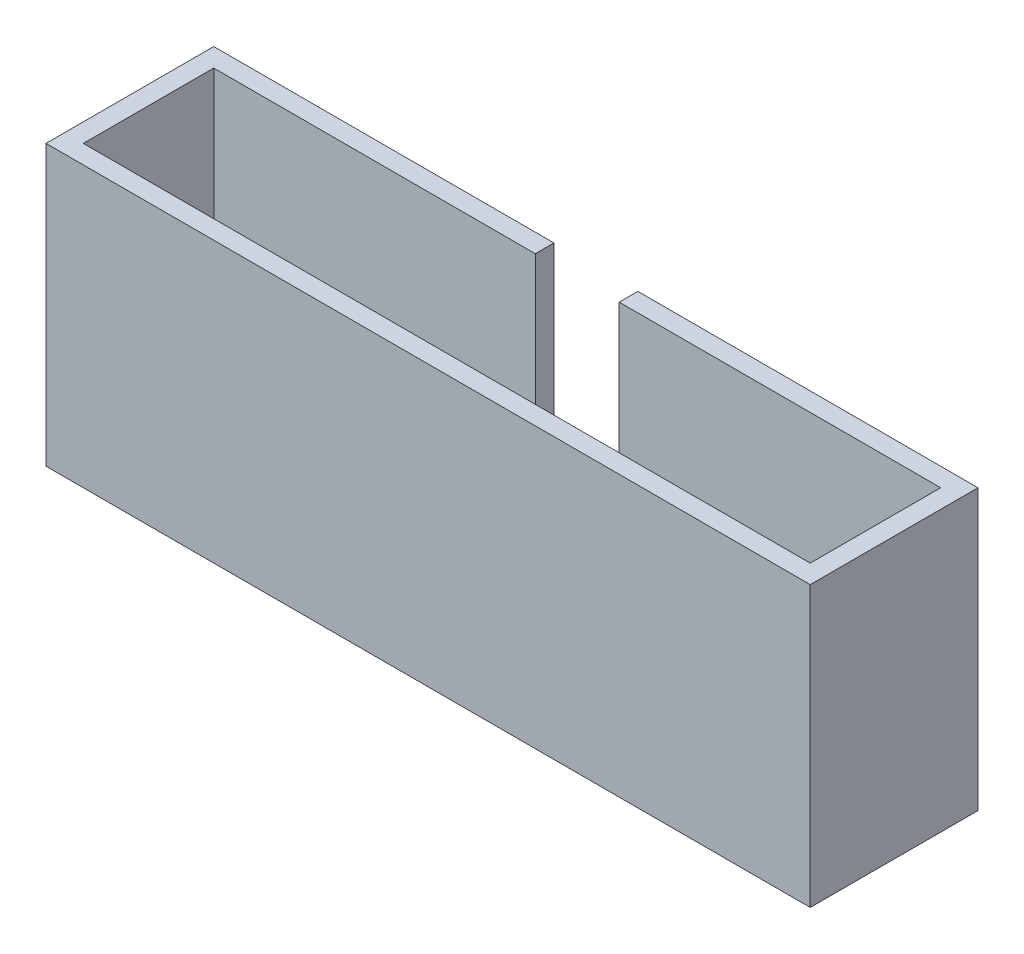
SolidWorks part; units mm, degrees
ref_plane "前视基准面" through (0, 0, 0) normal (0, 0, 1) x (1, 0, 0)
ref_plane "上视基准面" through (0, 0, 0) normal (0, 1, 0) x (1, 0, 0)
ref_plane "右视基准面" through (0, 0, 0) normal (1, 0, 0) x (0, 0, -1)
sketch "底图" plane through (0, 0, 0) normal (0, 1, 0) x (1, 0, 0)
  line L1 (19.5, -3.5) -> (-19.5, -3.5)
  line L2 (19.5, -3.5) -> (19.5, 3.5)
  line L3 (19.5, 3.5) -> (-19.5, 3.5)
  line L4 (-19.5, -3.5) -> (-19.5, 3.5)
  line L5 (19.5, -3.5) -> (-19.5, 3.5) construction
  line L6 (19.5, 3.5) -> (-19.5, -3.5) construction
  line L7 (20.5, -4.5) -> (-20.5, -4.5)
  line L8 (20.5, -4.5) -> (20.5, 4.5)
  line L9 (20.5, 4.5) -> (-20.5, 4.5)
  line L10 (-20.5, -4.5) -> (-20.5, 4.5)
  line L11 (20.5, -4.5) -> (-20.5, 4.5) construction
  line L12 (20.5, 4.5) -> (-20.5, -4.5) construction
  line L13 (2.25, -4.5) -> (-2.25, -4.5)
  line L14 (2.25, -4.5) -> (2.25, 4.5)
  line L15 (2.25, 4.5) -> (-2.25, 4.5)
  line L16 (-2.25, -4.5) -> (-2.25, 4.5)
  line L17 (2.25, -4.5) -> (-2.25, 4.5) construction
  line L18 (2.25, 4.5) -> (-2.25, -4.5) construction
  line L19 (-15, -1.25) -> (15, -1.25)
  line L20 (-15, -1.25) -> (-15, 1.25)
  line L21 (-15, 1.25) -> (15, 1.25)
  line L22 (15, -1.25) -> (15, 1.25)
  line L23 (-15, -1.25) -> (15, 1.25) construction
  line L24 (-15, 1.25) -> (15, -1.25) construction
  point P0 (0, 0)
  point P6 (0, 0)
  point P11 (0, 0)
  point P16 (0, 0)
  dimension "D1" = 7
  dimension "D2" = 39
  dimension "D3" = 41
  dimension "D4" = 9
  dimension "D5" = 4.5
  dimension "D6" = 9
  dimension "D7" = 2.5
  dimension "D8" = 30
sketch "基体" plane through (0, 0, 0) normal (0, 1, 0) x (1, 0, 0)
  line L4 (-2.25, -4.5) -> (2.25, -4.5)
  line L5 (-2.25, 4.5) -> (-2.25, -4.5)
  line L6 (2.25, 4.5) -> (-2.25, 4.5)
  line L7 (2.25, -4.5) -> (2.25, 4.5)
  line L8 (-2.25, -4.5) -> (2.25, -4.5)
  line L10 (2.25, 4.5) -> (-2.25, 4.5)
  line L12 (-20.5, -4.5) -> (20.5, -4.5)
  line L13 (-20.5, 4.5) -> (-20.5, -4.5)
  line L14 (20.5, 4.5) -> (-20.5, 4.5)
  line L15 (20.5, -4.5) -> (20.5, 4.5)
  line L16 (-20.5, -4.5) -> (20.5, -4.5)
  line L17 (-20.5, 4.5) -> (-20.5, -4.5)
  line L18 (20.5, 4.5) -> (-20.5, 4.5)
  line L19 (20.5, -4.5) -> (20.5, 4.5)
  dimension "D1" = 0
  dimension "D2" = 0
extrude "基体-凸台-拉伸" add sketch "基体" along normal blind 15 contours L16 L19 L18 L10 L17 L8
sketch "草图4" plane through (0, 0, 0) normal (0, 1, 0) x (1, 0, 0)
  line L1 (19.5, -3.5) -> (-19.5, -3.5)
  line L2 (19.5, -3.5) -> (19.5, 3.5)
  line L3 (19.5, 3.5) -> (-19.5, 3.5)
  line L4 (-19.5, -3.5) -> (-19.5, 3.5)
  line L5 (19.5, -3.5) -> (-19.5, 3.5) construction
  line L6 (19.5, 3.5) -> (-19.5, -3.5) construction
  point P0 (0, 0)
  dimension "D1" = 7
  dimension "D2" = 39
extrude "切除-拉伸8" cut sketch "草图4" against normal blind 10 from offset 15
sketch "草图5" plane through (0, 15, 0) normal (0, 1, 0) x (1, 0, 0)
  line L0 (-2.25, 0) -> (2.25, 0)
  line L2 (2.25, 0) -> (2.25, 6.901)
  line L3 (2.25, 6.901) -> (-2.25, 6.901)
  line L4 (-2.25, 0) -> (-2.25, 6.901)
  line L5 (0, 0) -> (-2.25, 6.901) construction
  line L6 (2.25, 6.901) -> (0, 0) construction
  point P0 (0, 0)
  dimension "D1" = 4.5
extrude "切除-拉伸9" cut sketch "草图5" against normal blind 10
sketch "草图6" plane through (0, 5, 0) normal (0, 1, 0) x (1, 0, 0)
  line L0 (2.25, 1.75) -> (2.75, 1.75)
  line L1 (2.75, 1.25) -> (2.75, 1.75)
  line L2 (-0.25, 1.25) -> (0.25, 1.25)
  line L3 (-0.25, 1.25) -> (-0.25, 1.75)
  line L4 (-0.25, 1.75) -> (0.25, 1.75)
  line L5 (0.25, 1.25) -> (0.25, 1.75)
  line L6 (-0.25, 1.25) -> (0.25, 1.75) construction
  line L7 (-0.25, 1.75) -> (0.25, 1.25) construction
  line L8 (2.25, 1.25) -> (2.75, 1.25)
  line L9 (2.25, 1.25) -> (2.25, 1.75)
  line L10 (4.75, 1.75) -> (5.25, 1.75)
  line L11 (5.25, 1.25) -> (5.25, 1.75)
  line L12 (4.75, 1.25) -> (5.25, 1.25)
  line L13 (4.75, 1.25) -> (4.75, 1.75)
  line L14 (7.25, 1.75) -> (7.75, 1.75)
  line L15 (7.75, 1.25) -> (7.75, 1.75)
  line L16 (7.25, 1.25) -> (7.75, 1.25)
  line L17 (7.25, 1.25) -> (7.25, 1.75)
  line L18 (9.75, 1.75) -> (10.25, 1.75)
  line L19 (10.25, 1.25) -> (10.25, 1.75)
  line L20 (9.75, 1.25) -> (10.25, 1.25)
  line L21 (9.75, 1.25) -> (9.75, 1.75)
  line L22 (12.25, 1.75) -> (12.75, 1.75)
  line L23 (12.75, 1.25) -> (12.75, 1.75)
  line L24 (12.25, 1.25) -> (12.75, 1.25)
  line L25 (12.25, 1.25) -> (12.25, 1.75)
  line L26 (14.75, 1.75) -> (15.25, 1.75)
  line L27 (15.25, 1.25) -> (15.25, 1.75)
  line L28 (14.75, 1.25) -> (15.25, 1.25)
  line L29 (14.75, 1.25) -> (14.75, 1.75)
  line L30 (-0.25, 1.75) -> (0.25, 1.75)
  line L31 (0.25, 1.25) -> (0.25, 1.75)
  line L32 (-0.25, 1.25) -> (0.25, 1.25)
  line L33 (-0.25, 1.25) -> (-0.25, 1.75)
  line L34 (2.25, 1.75) -> (2.75, 1.75)
  line L35 (2.75, 1.25) -> (2.75, 1.75)
  line L36 (2.25, 1.25) -> (2.75, 1.25)
  line L37 (2.25, 1.25) -> (2.25, 1.75)
  line L38 (4.75, 1.75) -> (5.25, 1.75)
  line L39 (5.25, 1.25) -> (5.25, 1.75)
  line L40 (4.75, 1.25) -> (5.25, 1.25)
  line L41 (4.75, 1.25) -> (4.75, 1.75)
  line L42 (7.25, 1.75) -> (7.75, 1.75)
  line L43 (7.75, 1.25) -> (7.75, 1.75)
  line L44 (7.25, 1.25) -> (7.75, 1.25)
  line L45 (7.25, 1.25) -> (7.25, 1.75)
  line L46 (9.75, 1.75) -> (10.25, 1.75)
  line L47 (10.25, 1.25) -> (10.25, 1.75)
  line L48 (9.75, 1.25) -> (10.25, 1.25)
  line L49 (9.75, 1.25) -> (9.75, 1.75)
  line L50 (12.25, 1.75) -> (12.75, 1.75)
  line L51 (12.75, 1.25) -> (12.75, 1.75)
  line L52 (12.25, 1.25) -> (12.75, 1.25)
  line L53 (12.25, 1.25) -> (12.25, 1.75)
  line L54 (-2.75, 1.75) -> (-2.25, 1.75)
  line L55 (-2.25, 1.25) -> (-2.25, 1.75)
  line L56 (-2.75, 1.25) -> (-2.25, 1.25)
  line L57 (-2.75, 1.25) -> (-2.75, 1.75)
  line L58 (-0.25, 1.75) -> (0.25, 1.75)
  line L59 (0.25, 1.25) -> (0.25, 1.75)
  line L60 (-0.25, 1.25) -> (0.25, 1.25)
  line L61 (-0.25, 1.25) -> (-0.25, 1.75)
  line L62 (2.25, 1.75) -> (2.75, 1.75)
  line L63 (2.75, 1.25) -> (2.75, 1.75)
  line L64 (2.25, 1.25) -> (2.75, 1.25)
  line L65 (2.25, 1.25) -> (2.25, 1.75)
  line L66 (4.75, 1.75) -> (5.25, 1.75)
  line L67 (5.25, 1.25) -> (5.25, 1.75)
  line L68 (4.75, 1.25) -> (5.25, 1.25)
  line L69 (4.75, 1.25) -> (4.75, 1.75)
  line L70 (7.25, 1.75) -> (7.75, 1.75)
  line L71 (7.75, 1.25) -> (7.75, 1.75)
  line L72 (7.25, 1.25) -> (7.75, 1.25)
  line L73 (7.25, 1.25) -> (7.25, 1.75)
  line L74 (9.75, 1.75) -> (10.25, 1.75)
  line L75 (10.25, 1.25) -> (10.25, 1.75)
  line L76 (9.75, 1.25) -> (10.25, 1.25)
  line L77 (9.75, 1.25) -> (9.75, 1.75)
  line L78 (-5.25, 1.75) -> (-4.75, 1.75)
  line L79 (-4.75, 1.25) -> (-4.75, 1.75)
  line L80 (-5.25, 1.25) -> (-4.75, 1.25)
  line L81 (-5.25, 1.25) -> (-5.25, 1.75)
  line L82 (-2.75, 1.75) -> (-2.25, 1.75)
  line L83 (-2.25, 1.25) -> (-2.25, 1.75)
  line L84 (-2.75, 1.25) -> (-2.25, 1.25)
  line L85 (-2.75, 1.25) -> (-2.75, 1.75)
  line L86 (-0.25, 1.75) -> (0.25, 1.75)
  line L87 (0.25, 1.25) -> (0.25, 1.75)
  line L88 (-0.25, 1.25) -> (0.25, 1.25)
  line L89 (-0.25, 1.25) -> (-0.25, 1.75)
  line L90 (2.25, 1.75) -> (2.75, 1.75)
  line L91 (2.75, 1.25) -> (2.75, 1.75)
  line L92 (2.25, 1.25) -> (2.75, 1.25)
  line L93 (2.25, 1.25) -> (2.25, 1.75)
  line L94 (4.75, 1.75) -> (5.25, 1.75)
  line L95 (5.25, 1.25) -> (5.25, 1.75)
  line L96 (4.75, 1.25) -> (5.25, 1.25)
  line L97 (4.75, 1.25) -> (4.75, 1.75)
  line L98 (7.25, 1.75) -> (7.75, 1.75)
  line L99 (7.75, 1.25) -> (7.75, 1.75)
  line L100 (7.25, 1.25) -> (7.75, 1.25)
  line L101 (7.25, 1.25) -> (7.25, 1.75)
  line L102 (-7.75, 1.75) -> (-7.25, 1.75)
  line L103 (-7.25, 1.25) -> (-7.25, 1.75)
  line L104 (-7.75, 1.25) -> (-7.25, 1.25)
  line L105 (-7.75, 1.25) -> (-7.75, 1.75)
  line L106 (-5.25, 1.75) -> (-4.75, 1.75)
  line L107 (-4.75, 1.25) -> (-4.75, 1.75)
  line L108 (-5.25, 1.25) -> (-4.75, 1.25)
  line L109 (-5.25, 1.25) -> (-5.25, 1.75)
  line L110 (-2.75, 1.75) -> (-2.25, 1.75)
  line L111 (-2.25, 1.25) -> (-2.25, 1.75)
  line L112 (-2.75, 1.25) -> (-2.25, 1.25)
  line L113 (-2.75, 1.25) -> (-2.75, 1.75)
  line L114 (-0.25, 1.75) -> (0.25, 1.75)
  line L115 (0.25, 1.25) -> (0.25, 1.75)
  line L116 (-0.25, 1.25) -> (0.25, 1.25)
  line L117 (-0.25, 1.25) -> (-0.25, 1.75)
  line L118 (2.25, 1.75) -> (2.75, 1.75)
  line L119 (2.75, 1.25) -> (2.75, 1.75)
  line L120 (2.25, 1.25) -> (2.75, 1.25)
  line L121 (2.25, 1.25) -> (2.25, 1.75)
  line L122 (4.75, 1.75) -> (5.25, 1.75)
  line L123 (5.25, 1.25) -> (5.25, 1.75)
  line L124 (4.75, 1.25) -> (5.25, 1.25)
  line L125 (4.75, 1.25) -> (4.75, 1.75)
  line L126 (-10.25, 1.75) -> (-9.75, 1.75)
  line L127 (-9.75, 1.25) -> (-9.75, 1.75)
  line L128 (-10.25, 1.25) -> (-9.75, 1.25)
  line L129 (-10.25, 1.25) -> (-10.25, 1.75)
  line L130 (-7.75, 1.75) -> (-7.25, 1.75)
  line L131 (-7.25, 1.25) -> (-7.25, 1.75)
  line L132 (-7.75, 1.25) -> (-7.25, 1.25)
  line L133 (-7.75, 1.25) -> (-7.75, 1.75)
  line L134 (-5.25, 1.75) -> (-4.75, 1.75)
  line L135 (-4.75, 1.25) -> (-4.75, 1.75)
  line L136 (-5.25, 1.25) -> (-4.75, 1.25)
  line L137 (-5.25, 1.25) -> (-5.25, 1.75)
  line L138 (-2.75, 1.75) -> (-2.25, 1.75)
  line L139 (-2.25, 1.25) -> (-2.25, 1.75)
  line L140 (-2.75, 1.25) -> (-2.25, 1.25)
  line L141 (-2.75, 1.25) -> (-2.75, 1.75)
  line L142 (-0.25, 1.75) -> (0.25, 1.75)
  line L143 (0.25, 1.25) -> (0.25, 1.75)
  line L144 (-0.25, 1.25) -> (0.25, 1.25)
  line L145 (-0.25, 1.25) -> (-0.25, 1.75)
  line L146 (2.25, 1.75) -> (2.75, 1.75)
  line L147 (2.75, 1.25) -> (2.75, 1.75)
  line L148 (2.25, 1.25) -> (2.75, 1.25)
  line L149 (2.25, 1.25) -> (2.25, 1.75)
  line L150 (-12.75, 1.75) -> (-12.25, 1.75)
  line L151 (-12.25, 1.25) -> (-12.25, 1.75)
  line L152 (-12.75, 1.25) -> (-12.25, 1.25)
  line L153 (-12.75, 1.25) -> (-12.75, 1.75)
  line L154 (-10.25, 1.75) -> (-9.75, 1.75)
  line L155 (-9.75, 1.25) -> (-9.75, 1.75)
  line L156 (-10.25, 1.25) -> (-9.75, 1.25)
  line L157 (-10.25, 1.25) -> (-10.25, 1.75)
  line L158 (-7.75, 1.75) -> (-7.25, 1.75)
  line L159 (-7.25, 1.25) -> (-7.25, 1.75)
  line L160 (-7.75, 1.25) -> (-7.25, 1.25)
  line L161 (-7.75, 1.25) -> (-7.75, 1.75)
  line L162 (-5.25, 1.75) -> (-4.75, 1.75)
  line L163 (-4.75, 1.25) -> (-4.75, 1.75)
  line L164 (-5.25, 1.25) -> (-4.75, 1.25)
  line L165 (-5.25, 1.25) -> (-5.25, 1.75)
  line L166 (-2.75, 1.75) -> (-2.25, 1.75)
  line L167 (-2.25, 1.25) -> (-2.25, 1.75)
  line L168 (-2.75, 1.25) -> (-2.25, 1.25)
  line L169 (-2.75, 1.25) -> (-2.75, 1.75)
  line L170 (-0.25, 1.75) -> (0.25, 1.75)
  line L171 (0.25, 1.25) -> (0.25, 1.75)
  line L172 (-0.25, 1.25) -> (0.25, 1.25)
  line L173 (-0.25, 1.25) -> (-0.25, 1.75)
  line L174 (-2.75, 1.75) -> (-2.25, 1.75)
  line L175 (-2.25, 1.25) -> (-2.25, 1.75)
  line L176 (-2.75, 1.25) -> (-2.25, 1.25)
  line L177 (-2.75, 1.25) -> (-2.75, 1.75)
  line L178 (-5.25, 1.75) -> (-4.75, 1.75)
  line L179 (-4.75, 1.25) -> (-4.75, 1.75)
  line L180 (-5.25, 1.25) -> (-4.75, 1.25)
  line L181 (-5.25, 1.25) -> (-5.25, 1.75)
  line L182 (-7.75, 1.75) -> (-7.25, 1.75)
  line L183 (-7.25, 1.25) -> (-7.25, 1.75)
  line L184 (-7.75, 1.25) -> (-7.25, 1.25)
  line L185 (-7.75, 1.25) -> (-7.75, 1.75)
  line L186 (-10.25, 1.75) -> (-9.75, 1.75)
  line L187 (-9.75, 1.25) -> (-9.75, 1.75)
  line L188 (-10.25, 1.25) -> (-9.75, 1.25)
  line L189 (-10.25, 1.25) -> (-10.25, 1.75)
  line L190 (-12.75, 1.75) -> (-12.25, 1.75)
  line L191 (-12.25, 1.25) -> (-12.25, 1.75)
  line L192 (-12.75, 1.25) -> (-12.25, 1.25)
  line L193 (-12.75, 1.25) -> (-12.75, 1.75)
  line L194 (-15.25, 1.75) -> (-14.75, 1.75)
  line L195 (-14.75, 1.25) -> (-14.75, 1.75)
  line L196 (-15.25, 1.25) -> (-14.75, 1.25)
  line L197 (-15.25, 1.25) -> (-15.25, 1.75)
  line L199 (-0.25, -1.75) -> (0.25, -1.25) construction
  line L200 (-0.25, -1.25) -> (0.25, -1.75) construction
  line L201 (-15.25, -1.25) -> (-15.25, -1.75)
  line L202 (-15.25, -1.25) -> (-14.75, -1.25)
  line L203 (-14.75, -1.25) -> (-14.75, -1.75)
  line L204 (-15.25, -1.75) -> (-14.75, -1.75)
  line L205 (-12.75, -1.25) -> (-12.75, -1.75)
  line L206 (-12.75, -1.25) -> (-12.25, -1.25)
  line L207 (-12.25, -1.25) -> (-12.25, -1.75)
  line L208 (-12.75, -1.75) -> (-12.25, -1.75)
  line L209 (-10.25, -1.25) -> (-10.25, -1.75)
  line L210 (-10.25, -1.25) -> (-9.75, -1.25)
  line L211 (-9.75, -1.25) -> (-9.75, -1.75)
  line L212 (-10.25, -1.75) -> (-9.75, -1.75)
  line L213 (-7.75, -1.25) -> (-7.75, -1.75)
  line L214 (-7.75, -1.25) -> (-7.25, -1.25)
  line L215 (-7.25, -1.25) -> (-7.25, -1.75)
  line L216 (-7.75, -1.75) -> (-7.25, -1.75)
  line L217 (-5.25, -1.25) -> (-5.25, -1.75)
  line L218 (-5.25, -1.25) -> (-4.75, -1.25)
  line L219 (-4.75, -1.25) -> (-4.75, -1.75)
  line L220 (-5.25, -1.75) -> (-4.75, -1.75)
  line L221 (-2.75, -1.25) -> (-2.75, -1.75)
  line L222 (-2.75, -1.25) -> (-2.25, -1.25)
  line L223 (-2.25, -1.25) -> (-2.25, -1.75)
  line L224 (-2.75, -1.75) -> (-2.25, -1.75)
  line L225 (-0.25, -1.25) -> (-0.25, -1.75)
  line L226 (-0.25, -1.25) -> (0.25, -1.25)
  line L227 (0.25, -1.25) -> (0.25, -1.75)
  line L228 (-0.25, -1.75) -> (0.25, -1.75)
  line L229 (-2.75, -1.25) -> (-2.75, -1.75)
  line L230 (-2.75, -1.25) -> (-2.25, -1.25)
  line L231 (-2.25, -1.25) -> (-2.25, -1.75)
  line L232 (-2.75, -1.75) -> (-2.25, -1.75)
  line L233 (-5.25, -1.25) -> (-5.25, -1.75)
  line L234 (-5.25, -1.25) -> (-4.75, -1.25)
  line L235 (-4.75, -1.25) -> (-4.75, -1.75)
  line L236 (-5.25, -1.75) -> (-4.75, -1.75)
  line L237 (-7.75, -1.25) -> (-7.75, -1.75)
  line L238 (-7.75, -1.25) -> (-7.25, -1.25)
  line L239 (-7.25, -1.25) -> (-7.25, -1.75)
  line L240 (-7.75, -1.75) -> (-7.25, -1.75)
  line L241 (-10.25, -1.25) -> (-10.25, -1.75)
  line L242 (-10.25, -1.25) -> (-9.75, -1.25)
  line L243 (-9.75, -1.25) -> (-9.75, -1.75)
  line L244 (-10.25, -1.75) -> (-9.75, -1.75)
  line L245 (-12.75, -1.25) -> (-12.75, -1.75)
  line L246 (-12.75, -1.25) -> (-12.25, -1.25)
  line L247 (-12.25, -1.25) -> (-12.25, -1.75)
  line L248 (-12.75, -1.75) -> (-12.25, -1.75)
  line L249 (2.25, -1.25) -> (2.25, -1.75)
  line L250 (2.25, -1.25) -> (2.75, -1.25)
  line L251 (2.75, -1.25) -> (2.75, -1.75)
  line L252 (2.25, -1.75) -> (2.75, -1.75)
  line L253 (-0.25, -1.25) -> (-0.25, -1.75)
  line L254 (-0.25, -1.25) -> (0.25, -1.25)
  line L255 (0.25, -1.25) -> (0.25, -1.75)
  line L256 (-0.25, -1.75) -> (0.25, -1.75)
  line L257 (-2.75, -1.25) -> (-2.75, -1.75)
  line L258 (-2.75, -1.25) -> (-2.25, -1.25)
  line L259 (-2.25, -1.25) -> (-2.25, -1.75)
  line L260 (-2.75, -1.75) -> (-2.25, -1.75)
  line L261 (-5.25, -1.25) -> (-5.25, -1.75)
  line L262 (-5.25, -1.25) -> (-4.75, -1.25)
  line L263 (-4.75, -1.25) -> (-4.75, -1.75)
  line L264 (-5.25, -1.75) -> (-4.75, -1.75)
  line L265 (-7.75, -1.25) -> (-7.75, -1.75)
  line L266 (-7.75, -1.25) -> (-7.25, -1.25)
  line L267 (-7.25, -1.25) -> (-7.25, -1.75)
  line L268 (-7.75, -1.75) -> (-7.25, -1.75)
  line L269 (-10.25, -1.25) -> (-10.25, -1.75)
  line L270 (-10.25, -1.25) -> (-9.75, -1.25)
  line L271 (-9.75, -1.25) -> (-9.75, -1.75)
  line L272 (-10.25, -1.75) -> (-9.75, -1.75)
  line L273 (4.75, -1.25) -> (4.75, -1.75)
  line L274 (4.75, -1.25) -> (5.25, -1.25)
  line L275 (5.25, -1.25) -> (5.25, -1.75)
  line L276 (4.75, -1.75) -> (5.25, -1.75)
  line L277 (2.25, -1.25) -> (2.25, -1.75)
  line L278 (2.25, -1.25) -> (2.75, -1.25)
  line L279 (2.75, -1.25) -> (2.75, -1.75)
  line L280 (2.25, -1.75) -> (2.75, -1.75)
  line L281 (-0.25, -1.25) -> (-0.25, -1.75)
  line L282 (-0.25, -1.25) -> (0.25, -1.25)
  line L283 (0.25, -1.25) -> (0.25, -1.75)
  line L284 (-0.25, -1.75) -> (0.25, -1.75)
  line L285 (-2.75, -1.25) -> (-2.75, -1.75)
  line L286 (-2.75, -1.25) -> (-2.25, -1.25)
  line L287 (-2.25, -1.25) -> (-2.25, -1.75)
  line L288 (-2.75, -1.75) -> (-2.25, -1.75)
  line L289 (-5.25, -1.25) -> (-5.25, -1.75)
  line L290 (-5.25, -1.25) -> (-4.75, -1.25)
  line L291 (-4.75, -1.25) -> (-4.75, -1.75)
  line L292 (-5.25, -1.75) -> (-4.75, -1.75)
  line L293 (-7.75, -1.25) -> (-7.75, -1.75)
  line L294 (-7.75, -1.25) -> (-7.25, -1.25)
  line L295 (-7.25, -1.25) -> (-7.25, -1.75)
  line L296 (-7.75, -1.75) -> (-7.25, -1.75)
  line L297 (7.25, -1.25) -> (7.25, -1.75)
  line L298 (7.25, -1.25) -> (7.75, -1.25)
  line L299 (7.75, -1.25) -> (7.75, -1.75)
  line L300 (7.25, -1.75) -> (7.75, -1.75)
  line L301 (4.75, -1.25) -> (4.75, -1.75)
  line L302 (4.75, -1.25) -> (5.25, -1.25)
  line L303 (5.25, -1.25) -> (5.25, -1.75)
  line L304 (4.75, -1.75) -> (5.25, -1.75)
  line L305 (2.25, -1.25) -> (2.25, -1.75)
  line L306 (2.25, -1.25) -> (2.75, -1.25)
  line L307 (2.75, -1.25) -> (2.75, -1.75)
  line L308 (2.25, -1.75) -> (2.75, -1.75)
  line L309 (-0.25, -1.25) -> (-0.25, -1.75)
  line L310 (-0.25, -1.25) -> (0.25, -1.25)
  line L311 (0.25, -1.25) -> (0.25, -1.75)
  line L312 (-0.25, -1.75) -> (0.25, -1.75)
  line L313 (-2.75, -1.25) -> (-2.75, -1.75)
  line L314 (-2.75, -1.25) -> (-2.25, -1.25)
  line L315 (-2.25, -1.25) -> (-2.25, -1.75)
  line L316 (-2.75, -1.75) -> (-2.25, -1.75)
  line L317 (-5.25, -1.25) -> (-5.25, -1.75)
  line L318 (-5.25, -1.25) -> (-4.75, -1.25)
  line L319 (-4.75, -1.25) -> (-4.75, -1.75)
  line L320 (-5.25, -1.75) -> (-4.75, -1.75)
  line L321 (9.75, -1.25) -> (9.75, -1.75)
  line L322 (9.75, -1.25) -> (10.25, -1.25)
  line L323 (10.25, -1.25) -> (10.25, -1.75)
  line L324 (9.75, -1.75) -> (10.25, -1.75)
  line L325 (7.25, -1.25) -> (7.25, -1.75)
  line L326 (7.25, -1.25) -> (7.75, -1.25)
  line L327 (7.75, -1.25) -> (7.75, -1.75)
  line L328 (7.25, -1.75) -> (7.75, -1.75)
  line L329 (4.75, -1.25) -> (4.75, -1.75)
  line L330 (4.75, -1.25) -> (5.25, -1.25)
  line L331 (5.25, -1.25) -> (5.25, -1.75)
  line L332 (4.75, -1.75) -> (5.25, -1.75)
  line L333 (2.25, -1.25) -> (2.25, -1.75)
  line L334 (2.25, -1.25) -> (2.75, -1.25)
  line L335 (2.75, -1.25) -> (2.75, -1.75)
  line L336 (2.25, -1.75) -> (2.75, -1.75)
  line L337 (-0.25, -1.25) -> (-0.25, -1.75)
  line L338 (-0.25, -1.25) -> (0.25, -1.25)
  line L339 (0.25, -1.25) -> (0.25, -1.75)
  line L340 (-0.25, -1.75) -> (0.25, -1.75)
  line L341 (-2.75, -1.25) -> (-2.75, -1.75)
  line L342 (-2.75, -1.25) -> (-2.25, -1.25)
  line L343 (-2.25, -1.25) -> (-2.25, -1.75)
  line L344 (-2.75, -1.75) -> (-2.25, -1.75)
  line L345 (12.25, -1.25) -> (12.25, -1.75)
  line L346 (12.25, -1.25) -> (12.75, -1.25)
  line L347 (12.75, -1.25) -> (12.75, -1.75)
  line L348 (12.25, -1.75) -> (12.75, -1.75)
  line L349 (9.75, -1.25) -> (9.75, -1.75)
  line L350 (9.75, -1.25) -> (10.25, -1.25)
  line L351 (10.25, -1.25) -> (10.25, -1.75)
  line L352 (9.75, -1.75) -> (10.25, -1.75)
  line L353 (7.25, -1.25) -> (7.25, -1.75)
  line L354 (7.25, -1.25) -> (7.75, -1.25)
  line L355 (7.75, -1.25) -> (7.75, -1.75)
  line L356 (7.25, -1.75) -> (7.75, -1.75)
  line L357 (4.75, -1.25) -> (4.75, -1.75)
  line L358 (4.75, -1.25) -> (5.25, -1.25)
  line L359 (5.25, -1.25) -> (5.25, -1.75)
  line L360 (4.75, -1.75) -> (5.25, -1.75)
  line L361 (2.25, -1.25) -> (2.25, -1.75)
  line L362 (2.25, -1.25) -> (2.75, -1.25)
  line L363 (2.75, -1.25) -> (2.75, -1.75)
  line L364 (2.25, -1.75) -> (2.75, -1.75)
  line L365 (-0.25, -1.25) -> (-0.25, -1.75)
  line L366 (-0.25, -1.25) -> (0.25, -1.25)
  line L367 (0.25, -1.25) -> (0.25, -1.75)
  line L368 (-0.25, -1.75) -> (0.25, -1.75)
  line L369 (14.75, -1.25) -> (14.75, -1.75)
  line L370 (14.75, -1.25) -> (15.25, -1.25)
  line L371 (15.25, -1.25) -> (15.25, -1.75)
  line L372 (14.75, -1.75) -> (15.25, -1.75)
  line L373 (12.25, -1.25) -> (12.25, -1.75)
  line L374 (12.25, -1.25) -> (12.75, -1.25)
  line L375 (12.75, -1.25) -> (12.75, -1.75)
  line L376 (12.25, -1.75) -> (12.75, -1.75)
  line L377 (9.75, -1.25) -> (9.75, -1.75)
  line L378 (9.75, -1.25) -> (10.25, -1.25)
  line L379 (10.25, -1.25) -> (10.25, -1.75)
  line L380 (9.75, -1.75) -> (10.25, -1.75)
  line L381 (7.25, -1.25) -> (7.25, -1.75)
  line L382 (7.25, -1.25) -> (7.75, -1.25)
  line L383 (7.75, -1.25) -> (7.75, -1.75)
  line L384 (7.25, -1.75) -> (7.75, -1.75)
  line L385 (4.75, -1.25) -> (4.75, -1.75)
  line L386 (4.75, -1.25) -> (5.25, -1.25)
  line L387 (5.25, -1.25) -> (5.25, -1.75)
  line L388 (4.75, -1.75) -> (5.25, -1.75)
  line L389 (2.25, -1.25) -> (2.25, -1.75)
  line L390 (2.25, -1.25) -> (2.75, -1.25)
  line L391 (0.25, -1.25) -> (0.25, -1.75)
  line L392 (-0.25, -1.75) -> (0.25, -1.75)
  line L393 (-0.25, -1.25) -> (-0.25, -1.75)
  line L394 (-0.25, -1.25) -> (0.25, -1.25)
  line L395 (2.75, -1.25) -> (2.75, -1.75)
  line L396 (2.25, -1.75) -> (2.75, -1.75)
  dimension "D1" = 7
  dimension "D2" = 0.5
  dimension "D3" = 0.5
